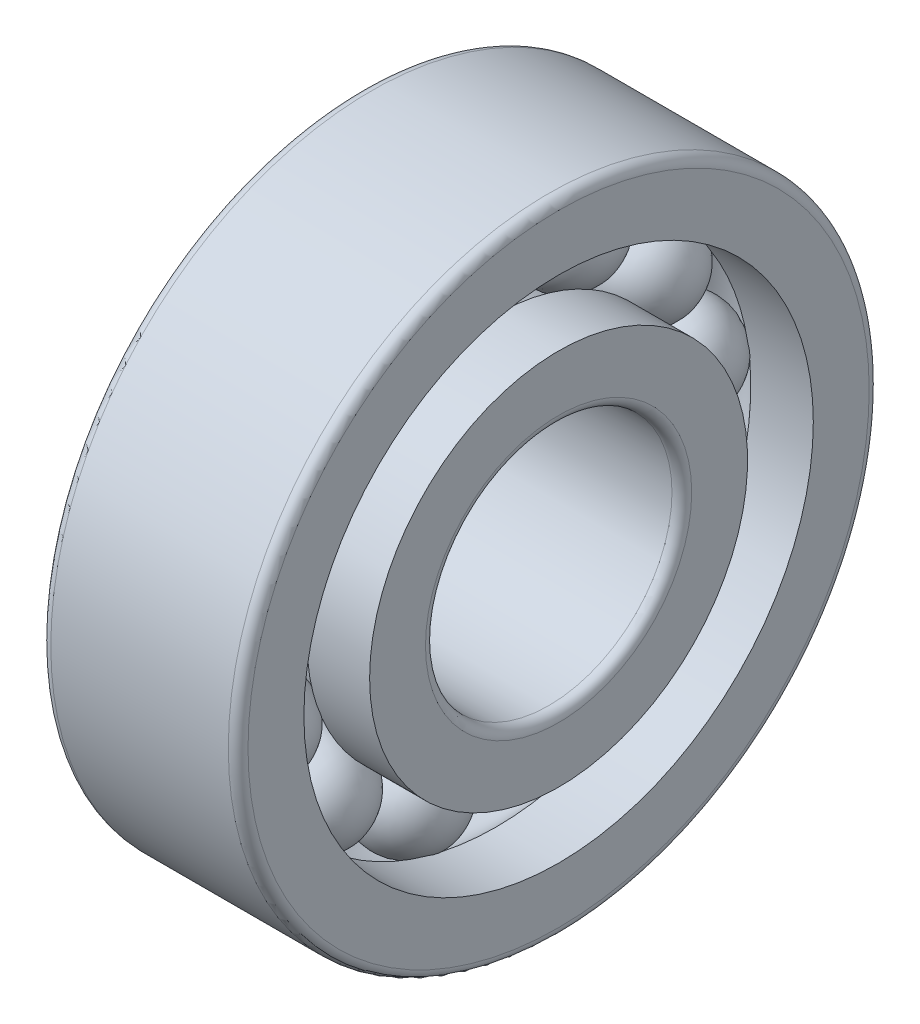
SolidWorks part; units mm, degrees
ref_plane "Front" through (0, 0, 0) normal (0, 0, 1) x (1, 0, 0)
ref_plane "Top" through (0, 0, 0) normal (0, 1, 0) x (1, 0, 0)
ref_plane "Right" through (0, 0, 0) normal (1, 0, 0) x (0, 0, -1)
sketch "Sketch1" plane through (0, 0, 0) normal (0, 0, 1) x (1, 0, 0)
  line L0 (-9.6833, 0) -> (9.8371, 0) construction
  line L1 (-1, 4.5) -> (1, 4.5)
  line L2 (-4.5966, 4.5) -> (4.6657, 4.5) construction
  arc A0 (1, 4.5) -> (-1, 4.5) centre (0, 4.5) ccw
  dimension "dia" = 2
  dimension "d0" = 9
revolve "Revolve1" add sketch "Sketch1" angle 360 about L2
sketch "Sketch2" plane through (0, 0, 0) normal (0, 0, 1) x (1, 0, 0)
  line L0 (-2, 3.8333) -> (-2, 2.5)
  line L1 (-2, 2.5) -> (2, 2.5)
  line L2 (2, 2.5) -> (2, 3.8333)
  line L3 (2, 3.8333) -> (0.7319, 3.8333)
  line L4 (-6.9714, 0) -> (8.1665, 0) construction
  line L5 (-6.7058, 4.5) -> (6.7058, 4.5) construction
  line L6 (-0.7319, 3.8333) -> (-2, 3.8333)
  arc A0 (-0.7319, 3.8333) -> (0.7319, 3.8333) centre (0, 4.5) ccw
  dimension "B" = 4
  dimension "B/2" = 2
  dimension "D5" = 1.98
  dimension "d" = 5
  dimension "D3" = 4.5
  dimension "D4" = 1.3333
revolve "Revolve2" add sketch "Sketch2" angle 360 about L4
sketch "Sketch3" plane through (0, 0, 0) normal (0, 0, 1) x (1, 0, 0)
  line L0 (-8.7107, 0) -> (9.1288, 0) construction
  line L1 (-2, 6.5) -> (2, 6.5)
  line L2 (-2, 6.5) -> (-2, 5.1667)
  line L3 (-2, 5.1667) -> (-0.7319, 5.1667)
  line L4 (2, 6.5) -> (2, 5.1667)
  line L5 (-7.2948, 4.5) -> (7.2948, 4.5) construction
  line L6 (0.7319, 5.1667) -> (2, 5.1667)
  arc A0 (0.7319, 5.1667) -> (-0.7319, 5.1667) centre (0, 4.5) ccw
  dimension "D1" = 1.98
  dimension "DD" = 13
  dimension "B" = 4
  dimension "D4" = 4.5
  dimension "D5" = 1.3333
  dimension "B/2" = 2
revolve "Revolve3" add sketch "Sketch3" angle 360 about L0
pattern_circular "Circular-Pattern1" count 13 over 360 about axis through (0, 0, 0) along (1, 0, 0) of "Revolve1"
fillet "Fillet1" radius 0.2 4 edges at (-2, 0, 2.5) (-2, 0, 6.5) (2, 0, 6.5) (2, 0, 2.5)
equation "\"d0@Sketch1\" = ( \"DD@Sketch3\" + \"d@Sketch2\" )  / 2"
equation "\"dia@Sketch1\" =  ( \"DD@Sketch3\" - \"d@Sketch2\" )  / 4"
equation "\"D3@Sketch2\" = ( \"DD@Sketch3\" + \"d@Sketch2\" )  / 2 / 2"
equation "\"D4@Sketch2\" = ( \"DD@Sketch3\" - \"d@Sketch2\" )  / 6"
equation "\"D5@Sketch2\" = \"dia@Sketch1\" - 0.02"
equation "\"B/2@Sketch2\" = \"B@Sketch2\" / 2"
equation "\"D4@Sketch3\" = ( \"DD@Sketch3\" + \"d@Sketch2\" )  / 2 / 2"
equation "\"D5@Sketch3\" = ( \"DD@Sketch3\" - \"d@Sketch2\" )  / 6"
equation "\"B@Sketch3\" = \"B@Sketch2\""
equation "\"B/2@Sketch3\" = \"B@Sketch3\" / 2"
equation "\"D1@Sketch3\" = \"dia@Sketch1\" - 0.02"
equation "\"m@Circular-Pattern1\" = int( 3.14159265 / atn(( \"dia@Sketch1\" / 2) / sqr(( \"DD@Sketch3\" + \"d@Sketch2\" )  / 2 * ( \"DD@Sketch3\" + \"d@Sketch2\" )  / 2/4 - ( \"dia@Sketch1\" / 2) *  ( \"dia@Sketch1\" / 2))))-1"
